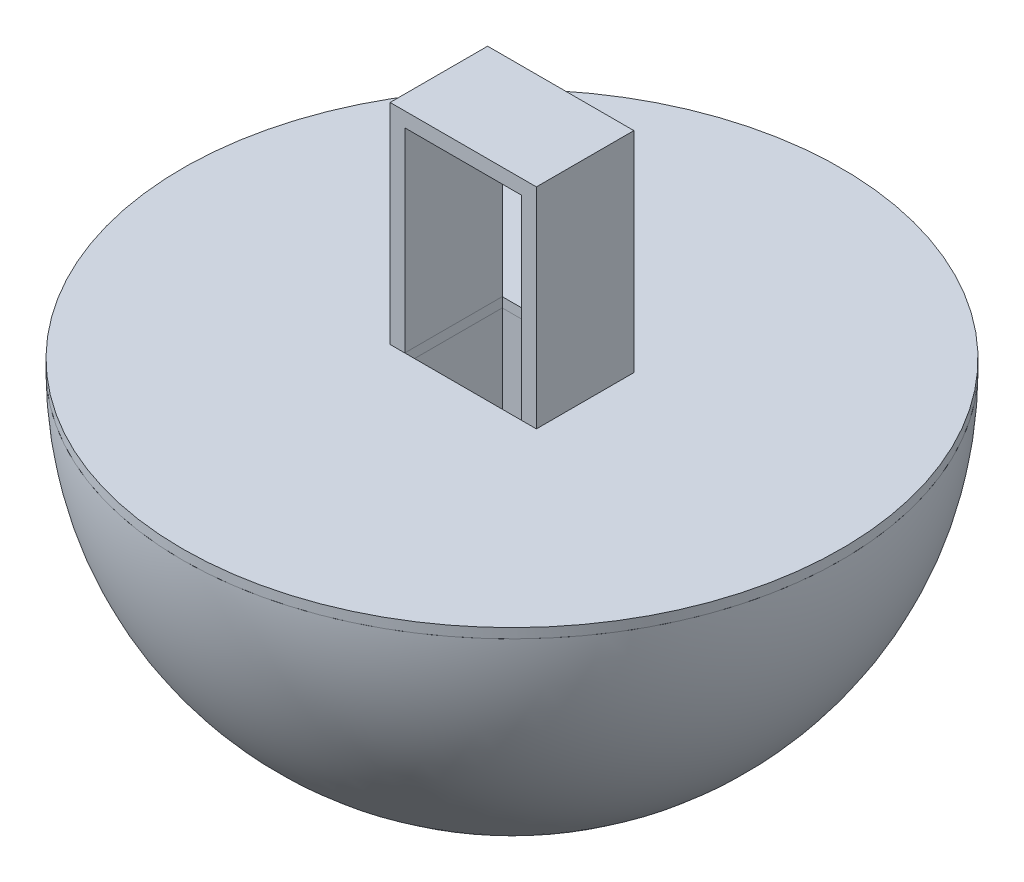
SolidWorks part; units mm, degrees
ref_plane "Front Plane" through (0, 0, 0) normal (0, 0, 1) x (1, 0, 0)
ref_plane "Top Plane" through (0, 0, 0) normal (0, 1, 0) x (1, 0, 0)
ref_plane "Right Plane" through (0, 0, 0) normal (1, 0, 0) x (0, 0, -1)
sketch "Sketch3" plane through (0, 0, 0) normal (1, 0, 0) x (0, 0, -1)
  line L0 (0, 0) -> (0, 33.8) construction
  line L1 (0, 33.8) -> (-33.8, 33.8)
  line L2 (0, 0) -> (0, 33.8)
  arc A0 (-33.8, 33.8) -> (0, 0) centre (0, 33.8) ccw
  dimension "D1" = 67.6
revolve "Revolve1" add sketch "Sketch3" angle 360 about L0
shell "Shell8" thickness 1
sketch "Sketch5" plane through (0, 33.8, 0) normal (0, 1, 0) x (1, 0, 0)
  line L0 (-7, -6) -> (-7, 6)
  line L1 (6, -5) -> (-6, -5)
  line L2 (6, -5) -> (6, 5)
  line L3 (6, 5) -> (-6, 5)
  line L4 (-6, -5) -> (-6, 5)
  line L5 (6, -5) -> (-6, 5) construction
  line L6 (6, 5) -> (-6, -5) construction
  line L7 (7, 6) -> (-7, 6)
  line L8 (7, -6) -> (7, 6)
  line L9 (7, -6) -> (-7, -6)
  point P1 (0, 0)
  dimension "D3" = 1
  dimension "D1" = 12
  dimension "D2" = 10
extrude "Boss-Extrude2" add sketch "Sketch5" against normal up to next
sketch "Sketch6" plane through (0, 33.8, 0) normal (0, 1, 0) x (1, 0, 0)
  line L4 (6, -5) -> (-6, -5)
  line L5 (6, 5) -> (6, -5)
  line L6 (-6, 5) -> (6, 5)
  line L7 (-6, -5) -> (-6, 5)
  line L8 (-6, -5) -> (-6, 5) construction
  line L9 (-6, -5) -> (-6, 5) construction
  circle A0 centre (0, 0) radius 4
  point P7 (4.5347, 3.4699)
  point P8 (-5.3648, 4)
  point P9 (-4.3872, -3.5109)
  point P10 (5.0985, -3.5109)
  point P11 (6, -5)
  point P13 (-6, -5)
  point P15 (-6, 5)
  point P20 (6, 5)
  point P22 (6, 5)
  point P23 (-6, 5)
  dimension "D1" = 8
extrude "Boss-Extrude3" add sketch "Sketch6" against normal up to next from offset 18 offset against normal yes
sketch "Sketch7" plane through (0, 15.8, 0) normal (0, 1, 0) x (1, 0, 0)
  circle A0 centre (0, 0) radius 1
  dimension "D1" = 2
extrude "Cut-Extrude3" cut sketch "Sketch7" against normal through all
sketch "Sketch8" plane through (0, 33.8, 0) normal (0, 1, 0) x (1, 0, 0)
  line L0 (6, -5) -> (6, 5) construction
  line L1 (-6, -5) -> (6, -5) construction
  line L2 (-6, 5) -> (-6, -5) construction
  line L3 (6, 5) -> (-6, 5) construction
  line L4 (6, -5) -> (6, 5)
  line L5 (-6, -5) -> (6, -5)
  line L6 (-6, 5) -> (-6, -5)
  line L7 (6, 5) -> (-6, 5)
  circle A1 centre (0, 0) radius 33.8
  circle A2 centre (0, 0) radius 33.8 construction
extrude "Boss-Extrude4" add sketch "Sketch8" along normal blind 1 separate body
ref_plane "Plane1" through (0, 1.2448, 0) normal (0, 1, 0) x (1, 0, 0)
sketch "Sketch10" plane through (0, 1.2448, 0) normal (0, 1, 0) x (1, 0, 0)
  line L1 (15, 15) -> (-15, 15)
  line L2 (15, 15) -> (15, -15)
  line L3 (15, -15) -> (-15, -15)
  line L4 (-15, 15) -> (-15, -15)
  line L5 (15, 15) -> (-15, -15) construction
  line L6 (15, -15) -> (-15, 15) construction
  point P0 (0, 0)
  dimension "D1" = 30
extrude "Cut-Extrude4" cut sketch "Sketch10" against normal through all
sketch "Sketch11" plane through (0, 34.8, 0) normal (0, 1, 0) x (1, 0, 0)
  line L11 (-6, -5) -> (6, -5) construction
  line L12 (-6, 5) -> (-7.5, 5)
  line L13 (-6, 5) -> (-6, -5)
  line L14 (-6, -5) -> (-7.5, -5)
  line L15 (-7.5, 5) -> (-7.5, -5)
  line L17 (6, 5) -> (7.5, 5)
  line L18 (6, 5) -> (6, -5)
  line L19 (6, -5) -> (7.5, -5)
  line L20 (7.5, 5) -> (7.5, -5)
  dimension "D1" = 1.5
extrude "Boss-Extrude5" add sketch "Sketch11" along normal blind 20 separate body
sketch "Sketch12" plane through (0, 54.8, 0) normal (0, 1, 0) x (1, 0, 0)
  line L1 (-7.5, 5) -> (7.5, 5)
  line L2 (-7.5, 5) -> (-7.5, -5)
  line L3 (-7.5, -5) -> (7.5, -5)
  line L4 (7.5, 5) -> (7.5, -5)
extrude "Boss-Extrude6" add sketch "Sketch12" along normal blind 1.5
